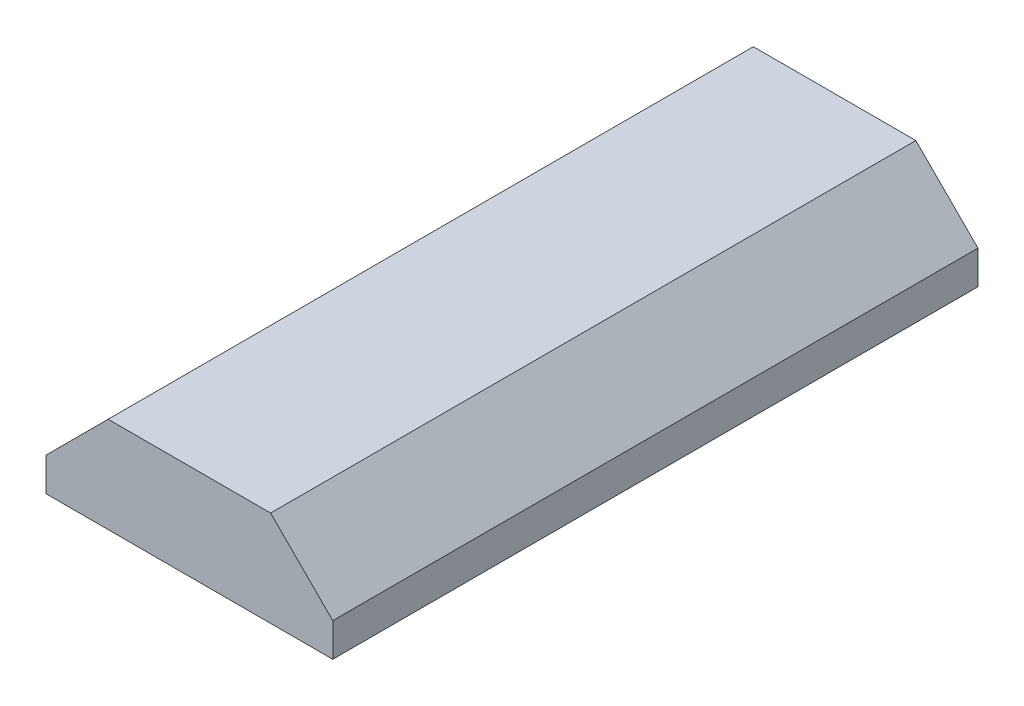
SolidWorks part; units mm, degrees
ref_plane "Ebene vorne" through (0, 0, 0) normal (0, 0, 1) x (1, 0, 0)
ref_plane "Ebene oben" through (0, 0, 0) normal (0, 1, 0) x (1, 0, 0)
ref_plane "Ebene rechts" through (0, 0, 0) normal (1, 0, 0) x (0, 0, -1)
sketch "Skizze1" plane through (0, 0, 0) normal (0, 0, 1) x (1, 0, 0)
  line L0 (0, 0) -> (0, 23680.6173) construction
  line L1 (3.4, 1.8089) -> (-3.4, 1.8089)
  line L2 (-3.4, 1.8089) -> (-6, -0.7911)
  line L3 (-6, -0.7911) -> (-6, -2.1911)
  line L4 (-6, -2.1911) -> (6, -2.1911)
  line L5 (6, -0.7911) -> (6, -2.1911)
  line L6 (3.4, 1.8089) -> (6, -0.7911)
  point P9 (0, -2.1911)
  point P11 (0, 1.8089)
  dimension "D1" = 3.4
  dimension "D2" = 6
  dimension "D3" = 4
  dimension "D4" = 135
extrude "Aufsatz-Linear austragen1" add sketch "Skizze1" along normal blind 27 contours L1 L2 L3 L4 L5 L6
